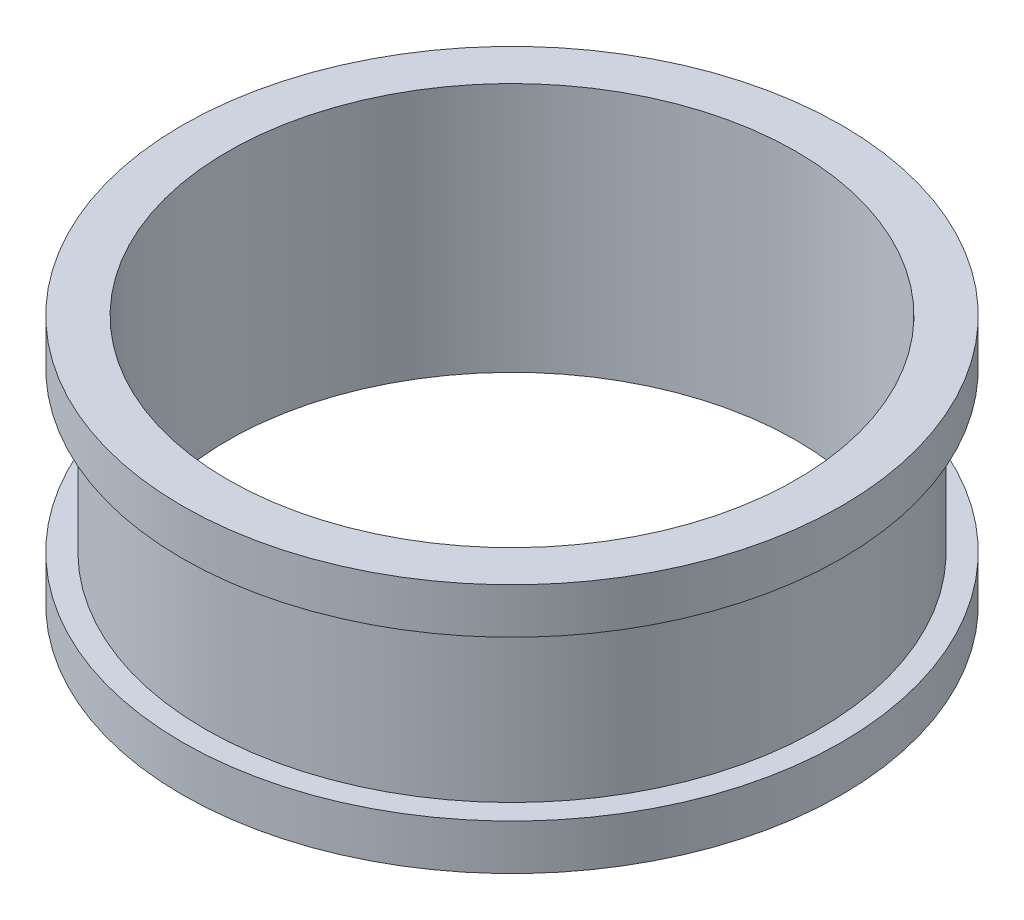
SolidWorks part; units mm, degrees
ref_plane "Top Plane" through (0, 0, 0) normal (0, 0, 1) x (1, 0, 0)
ref_plane "Front Plane" through (0, 0, 0) normal (0, 1, 0) x (1, 0, 0)
ref_plane "Right Plane" through (0, 0, 0) normal (1, 0, 0) x (0, 0, -1)
sketch "Sketch1" plane through (0, 0, 0) normal (0, 1, 0) x (1, 0, 0)
  circle A0 centre (0, 0) radius 14.5
  dimension "D1" = 29
extrude "Boss-Extrude1" add sketch "Sketch1" along normal blind 11
sketch "Sketch2" plane through (0, 0, 0) normal (0, -1, 0) x (1, 0, 0)
  circle A0 centre (0, 0) radius 12.5
  dimension "D1" = 25
extrude "Cut-Extrude1" cut sketch "Sketch2" against normal through all
sketch "Sketch3" plane through (0, 0, 0) normal (1, 0, 0) x (0, 0, -1)
  line L0 (0, 11.6409) -> (0, 0) construction
  line L1 (0, 6.05) -> (0, -6.05) construction
  line L2 (-14.5, 11) -> (-14.5, 9)
  line L3 (-14.5, 11) -> (-14.5, 0) construction
  line L4 (-14.5, 9) -> (-13.5, 9)
  line L5 (-13.5, 9) -> (-13.5, 2)
  line L6 (-13.5, 2) -> (-14.5, 2)
  line L7 (-14.5, 11) -> (-14.5, 0) construction
  line L8 (-14.5, 2) -> (-14.5, 0)
  line L9 (15.95, 0) -> (-15.95, 0) construction
  line L10 (-14.5, 11) -> (-14.5, 0) construction
  line L11 (14.5, 11) -> (-14.5, 11) construction
  line L12 (-14.5, 0) -> (-16.7293, 5.9957)
  line L13 (-16.7293, 5.9957) -> (-14.5, 11)
  dimension "D1" = 2
  dimension "D2" = 1
  dimension "D3" = 7
  dimension "D4" = 2
  dimension "D5" = 1
revolve "Cut-Revolve2" cut sketch "Sketch3" angle 360 about L0
